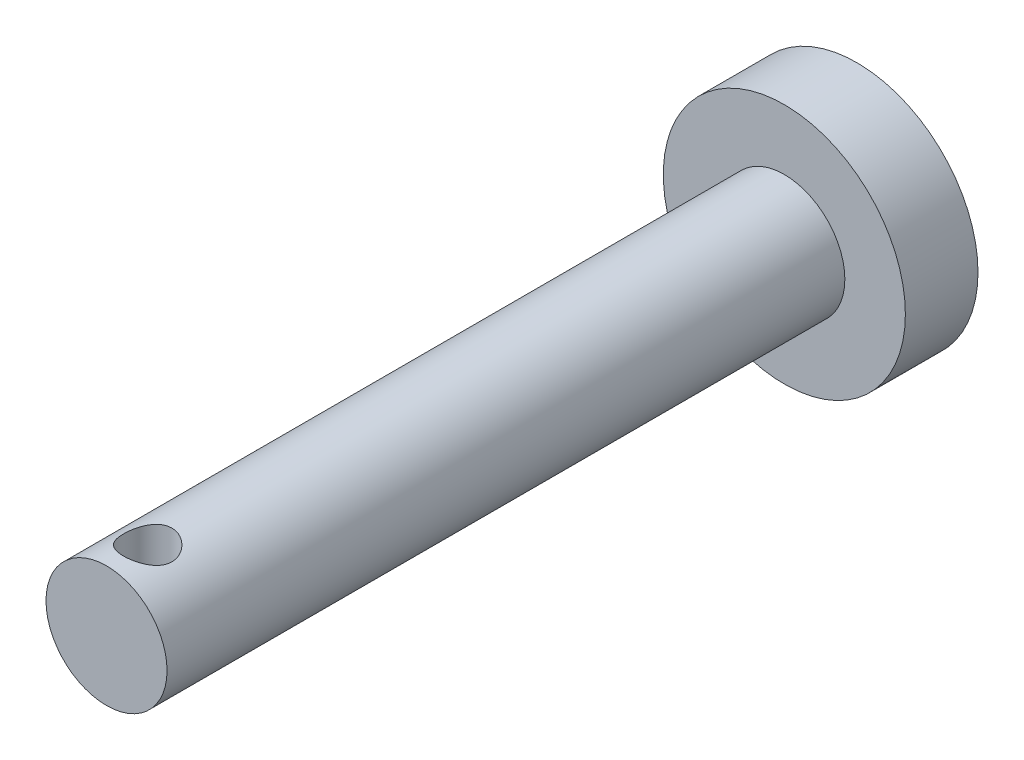
SolidWorks part; units mm, degrees
ref_plane "Front Plane" through (0, 0, 0) normal (0, 0, 1) x (1, 0, 0)
ref_plane "Top Plane" through (0, 0, 0) normal (0, 1, 0) x (1, 0, 0)
ref_plane "Right Plane" through (0, 0, 0) normal (1, 0, 0) x (0, 0, -1)
sketch "Sketch1" plane through (0, 0, 0) normal (1, 0, 0) x (0, 0, -1)
  line L0 (-80, 0) -> (80, 0) construction
  line L1 (80, 5) -> (80, -5) construction
  line L2 (80, 5) -> (77, 5) construction
  line L3 (-80, -2.5) -> (-80, 2.5) construction
  point P7 (-80, 0)
  dimension "Length" = 160
  dimension "Head Height" = 3
  dimension "Head Diameter" = 10
  dimension "Diameter" = 5
sketch "Sketch2" plane through (0, 0, 0) normal (1, 0, 0) x (0, 0, -1)
  line L0 (80, 0) -> (80, 5)
  line L1 (80, 5) -> (77, 5)
  line L2 (77, 5) -> (77, 2.5)
  line L3 (77, 2.5) -> (-80, 2.5)
  line L4 (-80, 2.5) -> (-80, 0)
  line L5 (-80, 0) -> (80, 0)
revolve "Revolve1" add sketch "Sketch2" angle 360 about L0
sketch "Sketch3" plane through (0, 0, 0) normal (1, 0, 0) x (0, 0, -1)
  line L1 (49, 5.7469) -> (-81, 5.7469)
  line L2 (49, 5.7469) -> (49, -5.5224)
  line L3 (49, -5.5224) -> (-81, -5.5224)
  line L4 (-81, 5.7469) -> (-81, -5.5224)
  line L5 (77, 5) -> (77, -5) construction
  line L6 (77, 0) -> (-80, 0) construction
  dimension "D1" = 28
  dimension "D2" = 130
  dimension "D3" = 11.2693
  dimension "D4" = 5.7469
extrude "Cut-Extrude1" cut sketch "Sketch3" against normal through all and the other way through all
sketch "Sketch4" plane through (0, 0, 0) normal (0, 1, 0) x (1, 0, 0)
  line L0 (-5, 77) -> (5, 77) construction
  line L1 (0, 77) -> (0, 49) construction
  circle A0 centre (0, 50.7) radius 1
  dimension "D1" = 2
  dimension "D2" = 26.3
  dimension "D3" = 0
extrude "Cut-Extrude2" cut sketch "Sketch4" against normal through all and the other way through all
